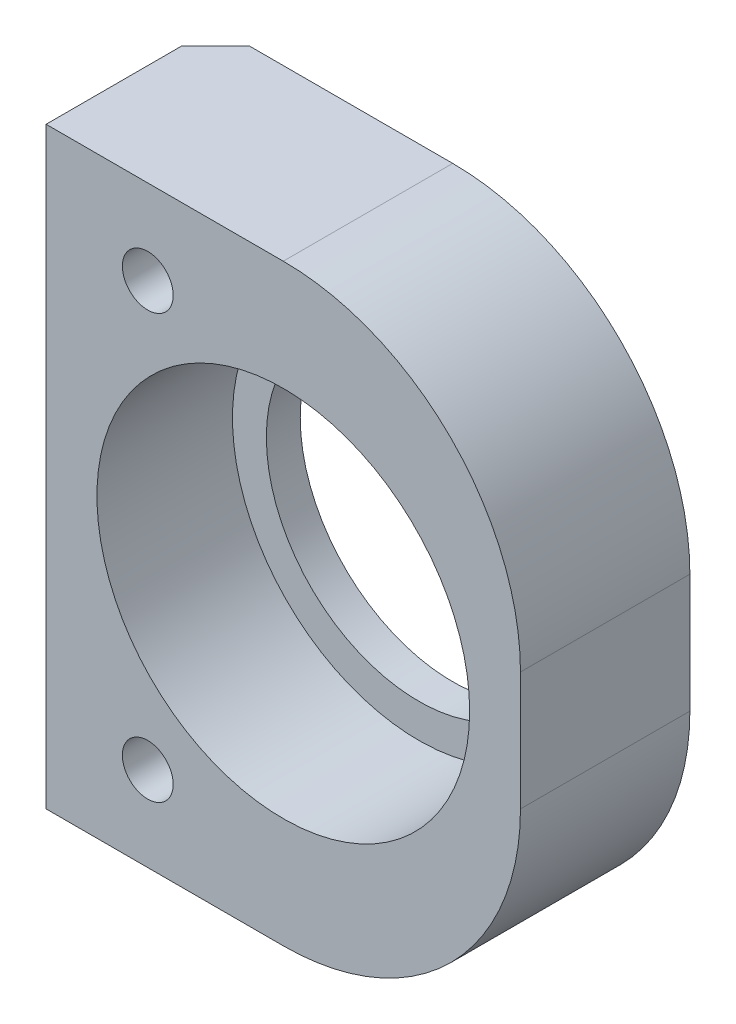
SolidWorks part; units mm, degrees
ref_plane "Alzado" through (0, 0, 0) normal (1, 0, 0) x (0, 1, 0)
ref_plane "Planta" through (0, 0, 0) normal (0, 0, 1) x (0, 1, 0)
ref_plane "Vista lateral" through (0, 0, 0) normal (0, 1, 0) x (-1, 0, 0)
sketch "Croquis1" plane through (0, 0, 0) normal (0, 0, 1) x (0, 1, 0)
  line L0 (0, 0) -> (0, 11) construction
  line L2 (17.5, 14) -> (-17.5, 14)
  line L3 (17.5, 14) -> (17.5, -14)
  line L4 (17.5, -14) -> (-17.5, -14)
  line L5 (-17.5, 14) -> (-17.5, -14)
  line L6 (0, -14) -> (0, 14) construction
  line L7 (17.5, 0) -> (-17.5, 0) construction
  circle A0 centre (0, 0) radius 11
  circle A1 centre (-12.5, 8) radius 1.5
  circle A2 centre (12.5, 8) radius 1.5
  dimension "D1" = 22
  dimension "D3" = 3
  dimension "D2" = 12.5
  dimension "D4" = 8
  dimension "D5" = 28
  dimension "D6" = 35
extrude "Saliente-Extruir1" add sketch "Croquis1" along normal blind 10
sketch "Croquis2" plane through (0, 0, 0) normal (0, 0, 1) x (0, 1, 0)
  circle A0 centre (0, 0) radius 9
  circle A1 centre (0, 0) radius 11
  dimension "D1" = 18
extrude "Saliente-Extruir2" add sketch "Croquis2" along normal blind 2
fillet "Redondeo1" radius 14 2 edges at (14, 17.5, 5) (14, -17.5, 5)
chamfer "Chaflán1" distance 2 angle 45 1 edges at (-14, 0, 0)
